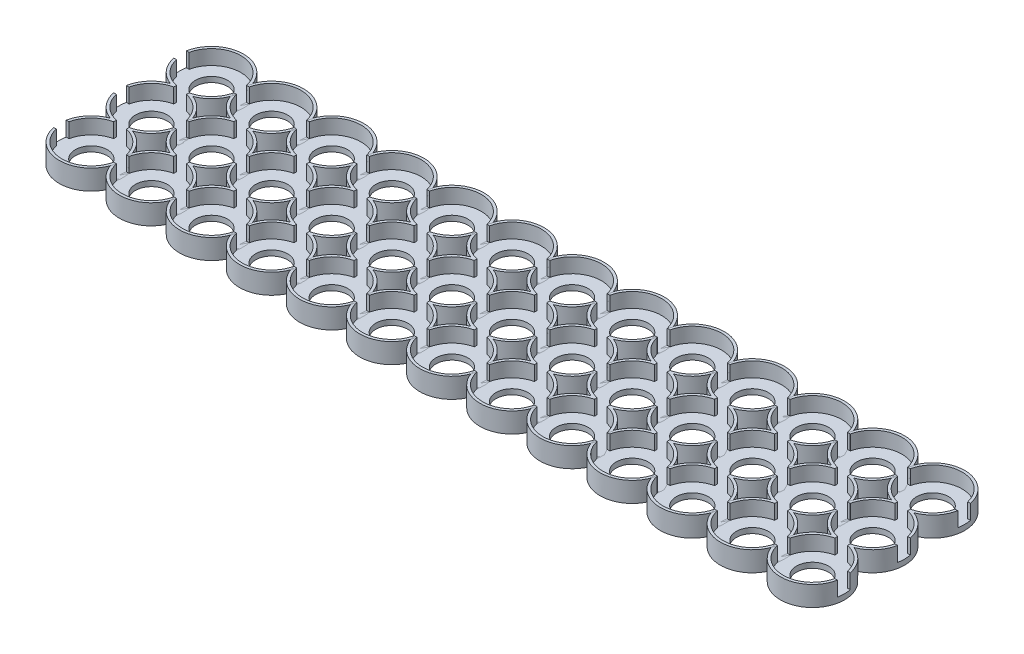
SolidWorks part; units mm, degrees
ref_plane "Front Plane" through (0, 0, 0) normal (0, 0, 1) x (1, 0, 0)
ref_plane "Top Plane" through (0, 0, 0) normal (0, 1, 0) x (1, 0, 0)
ref_plane "Right Plane" through (0, 0, 0) normal (1, 0, 0) x (0, 0, -1)
sketch "Sketch1" plane through (0, 0, 0) normal (1, 0, 0) x (0, 0, -1)
  line L0 (0, 27.0772) -> (0, -22.0037) construction
  line L1 (-12, 3.75) -> (-12, -3.75)
  line L2 (-12, -3.75) -> (-6, -3.75)
  line L3 (-6, -3.75) -> (-6, -1.75)
  line L4 (-6, -1.75) -> (-11, -1.75)
  line L5 (-11, -1.75) -> (-11, 3.75)
  line L6 (-11, 3.75) -> (-12, 3.75)
  point P5 (-12, 0)
  dimension "D1" = 7.5
  dimension "D2" = 2
  dimension "D3" = 22
  dimension "D4" = 12
  dimension "D5" = 1
revolve "Revolve1" add sketch "Sketch1" angle 360 about L0
sketch "Sketch2" plane through (0, -3.75, 0) normal (0, -1, 0) x (1, 0, 0)
  line L0 (0, 12.1827) -> (0, -11.4982) construction
pattern_linear "LPattern1" count 3 spacing 22.5 along (0, 0, -1) of "Revolve1"
sketch "Sketch3" plane through (0, -3.75, 0) normal (0, -1, 0) x (1, 0, 0)
  line L0 (-17.2986, 0) -> (17.8169, 0) construction
sketch "Sketch4" plane through (0, 3.75, 0) normal (0, 1, 0) x (1, 0, 0)
  line L0 (0, -12) -> (0, 57) construction
  arc A0 (-4.1758, 11.25) -> (4.1758, 11.25) centre (0, 0) ccw construction
  arc A1 (4.1758, 33.75) -> (-4.1758, 33.75) centre (0, 45) ccw construction
  dimension "D1" = 69
sketch "Sketch5" plane through (0, 3.75, 0) normal (0, 1, 0) x (1, 0, 0)
  line L0 (0, -12) -> (0, 57) construction
  line L1 (2.3825, 9.3948) -> (-2.3825, 9.3948)
  line L2 (2.3825, 9.3948) -> (2.3825, 20.125)
  line L3 (2.3825, 35.6052) -> (-2.3825, 35.6052)
  line L4 (-2.3825, 9.3948) -> (-2.3825, 20.125)
  line L5 (2.3825, 9.3948) -> (-2.3825, 35.6052) construction
  line L6 (2.3825, 35.6052) -> (-2.3825, 9.3948) construction
  line L7 (0, 22.5) -> (29.8045, 22.5) construction
  line L8 (-23.3563, 24.875) -> (-2.3825, 24.875)
  line L9 (-23.3563, 24.875) -> (-23.3563, 20.125)
  line L10 (-23.3563, 20.125) -> (-2.3825, 20.125)
  line L11 (19.6926, 24.875) -> (19.6926, 20.125)
  line L12 (0, 0) -> (26.7199, 0) construction
  line L13 (2.3793, 0) -> (32.1838, 0) construction
  line L14 (-23.3563, 2.375) -> (22.0719, 2.375)
  line L15 (-23.3563, 2.375) -> (-23.3563, -2.375)
  line L16 (-23.3563, -2.375) -> (22.0719, -2.375)
  line L17 (22.0719, 2.375) -> (22.0719, -2.375)
  line L18 (-23.3563, 42.625) -> (-23.3563, 47.375)
  line L19 (-23.3563, 47.375) -> (22.0719, 47.375)
  line L20 (22.0719, 42.625) -> (22.0719, 47.375)
  line L21 (-23.3563, 42.625) -> (22.0719, 42.625)
  line L23 (-2.3825, 24.875) -> (-2.3825, 35.6052)
  line L25 (2.3825, 20.125) -> (19.6926, 20.125)
  line L26 (2.3825, 24.875) -> (2.3825, 35.6052)
  line L27 (2.3825, 24.875) -> (19.6926, 24.875)
  point P0 (0, 22.5)
  point P17 (2.3793, -0.0228)
  dimension "D1" = 4.765
  dimension "D2" = 4.75
  dimension "D3" = 4.75
extrude "Cut-Extrude1" cut sketch "Sketch5" against normal up to surface (5.5 mm away) up to face at (0, -1.75, -45.25)
pattern_linear "LPattern2" count 13 spacing 22.5 along (1, 0, 0) of "Revolve1"
